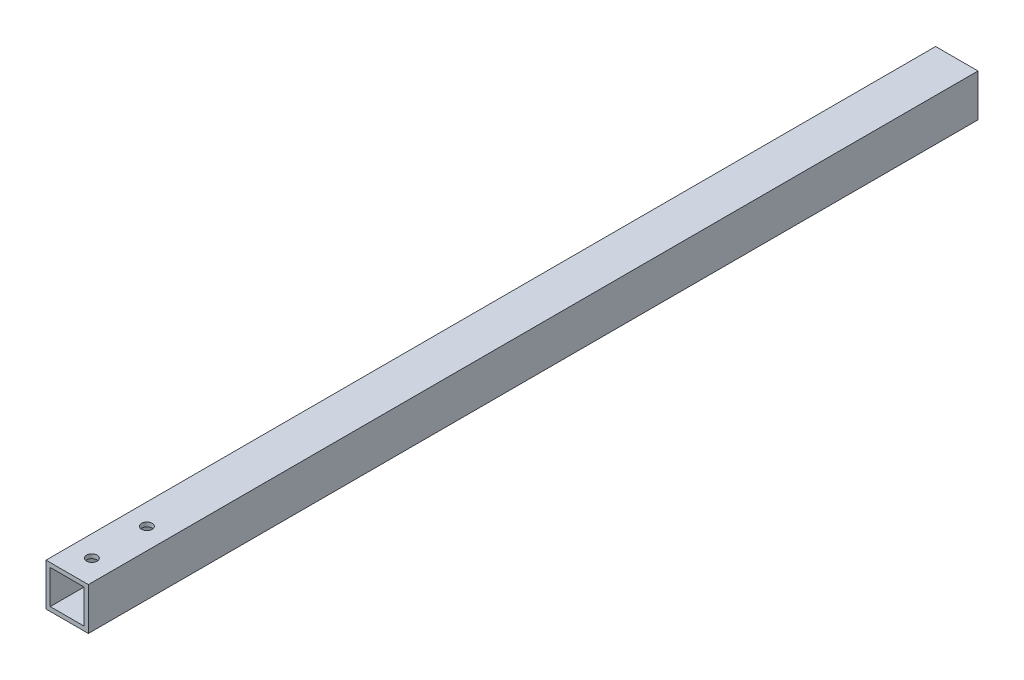
SolidWorks part; units mm, degrees
material "Thornel Mat VMA"
ref_plane "前视基准面" through (0, 0, 0) normal (0, 0, 1) x (1, 0, 0)
ref_plane "上视基准面" through (0, 0, 0) normal (0, 1, 0) x (1, 0, 0)
ref_plane "右视基准面" through (0, 0, 0) normal (1, 0, 0) x (0, 0, -1)
sketch "草图1" plane through (0, 0, 0) normal (0, 0, 1) x (1, 0, 0)
  line L1 (5, 5) -> (-5, 5)
  line L2 (5, 5) -> (5, -5)
  line L3 (5, -5) -> (-5, -5)
  line L4 (-5, 5) -> (-5, -5)
  line L5 (5, 5) -> (-5, -5) construction
  line L6 (5, -5) -> (-5, 5) construction
  line L7 (4, 4) -> (-4, 4)
  line L8 (4, 4) -> (4, -4)
  line L9 (4, -4) -> (-4, -4)
  line L10 (-4, 4) -> (-4, -4)
  line L11 (4, 4) -> (-4, -4) construction
  line L12 (4, -4) -> (-4, 4) construction
  point P0 (0, 0)
  point P6 (0, 0)
  dimension "D1" = 10
  dimension "D2" = 1
extrude "凸台-拉伸1" add sketch "草图1" along normal blind 210
hole_wizard "孔1" positions "草图2" profile "草图3" legacy end condition through all
sketch "草图2" plane through (0, -5, 0) normal (0, -1, 0) x (-1, 0, 0)
  point P0 (0, -204.1771)
  point P3 (0, -191.1771)
  point P6 (-130, -204.1771)
  point P9 (-130, -191.1771)
sketch "草图3" plane through (0, -5, 204.1771) normal (1, 0, 0) x (0, 0, -1)
  line L0 (0, 0) -> (0, 10)
  line L1 (0, 10) -> (1.25, 10)
  line L2 (1.25, 10) -> (1.25, 0)
  line L3 (1.25, 0) -> (0, 0)
  line L4 (0, 110) -> (0, -10) construction
  dimension "直径" = 2.5
  dimension "深度" = 10
